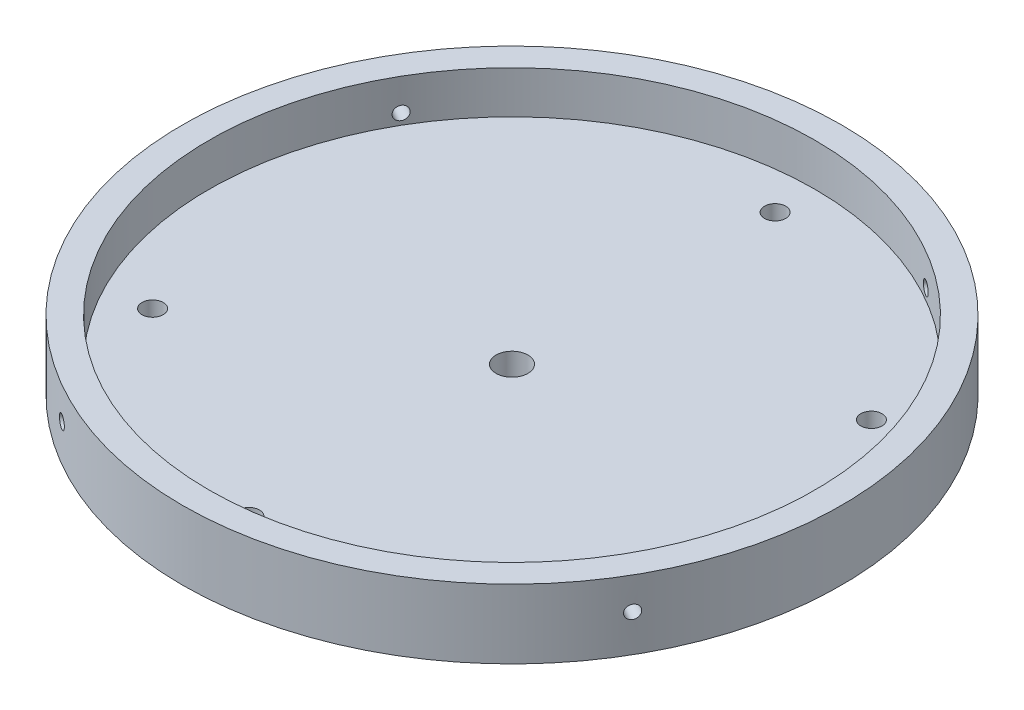
SolidWorks part; units mm, degrees
ref_plane "Front Plane" through (0, 0, 0) normal (0, 0, 1) x (1, 0, 0)
ref_plane "Top Plane" through (0, 0, 0) normal (0, 1, 0) x (1, 0, 0)
ref_plane "Right Plane" through (0, 0, 0) normal (1, 0, 0) x (0, 0, -1)
sketch "Sketch1" plane through (0, 0, 0) normal (0, 1, 0) x (1, 0, 0)
  circle A0 centre (0, 0) radius 62
  dimension "D1" = 124
extrude "Boss-Extrude1" add sketch "Sketch1" along normal blind 5
sketch "Sketch2" plane through (0, 5, 0) normal (0, 1, 0) x (1, 0, 0)
  circle A0 centre (0, 49.5) radius 2
  dimension "D2" = 4
  dimension "D1" = 49.5
extrude "Cut-Extrude1" cut sketch "Sketch2" against normal blind 5 contours A0
pattern_circular "CirPattern1" count 2 every 120 about axis through (0, 5, 0) along (0, 1, 0) of "Cut-Extrude1"
sketch "Sketch4" plane through (0, 5, 0) normal (0, 1, 0) x (1, 0, 0)
  line L0 (0, 49.5) -> (-42.8683, -24.75) construction
  line L1 (0, 0) -> (-23.6703, -40.9981) construction
ref_plane "Plane1" through (0, 0, 0) normal (-0.866, 0, -0.5) x (-0.5, 0, 0.866)
mirror "Mirror1" about plane through (0, 0, 0) normal (-0.866, 0, -0.5) of "Cut-Extrude1", "CirPattern1"
sketch "Sketch5" plane through (0, 5, 0) normal (0, 1, 0) x (1, 0, 0)
  circle A0 centre (0, 0) radius 62
  circle A1 centre (0, 0) radius 57
  dimension "D1" = 5
extrude "Boss-Extrude2" add sketch "Sketch5" along normal blind 8
sketch "Sketch6" plane through (0, 0, 0) normal (-0.866, 0, -0.5) x (-0.5, 0, 0.866)
  line L0 (57, 13) -> (-57, 13) construction
  circle A0 centre (0, 7) radius 1.25
  dimension "D1" = 2.5
  dimension "D2" = 6
extrude "Cut-Extrude2" cut sketch "Sketch6" against normal blind 90 and the other way blind 102 contours A0
pattern_circular "CirPattern2" count 2 every 90 about axis through (0, 13, 0) along (0, 1, 0) of "Cut-Extrude2"
sketch "Sketch7" plane through (0, 5, 0) normal (0, 1, 0) x (1, 0, 0)
  circle A0 centre (0, 0) radius 3
  dimension "D1" = 6
extrude "Cut-Extrude3" cut sketch "Sketch7" against normal blind 10
